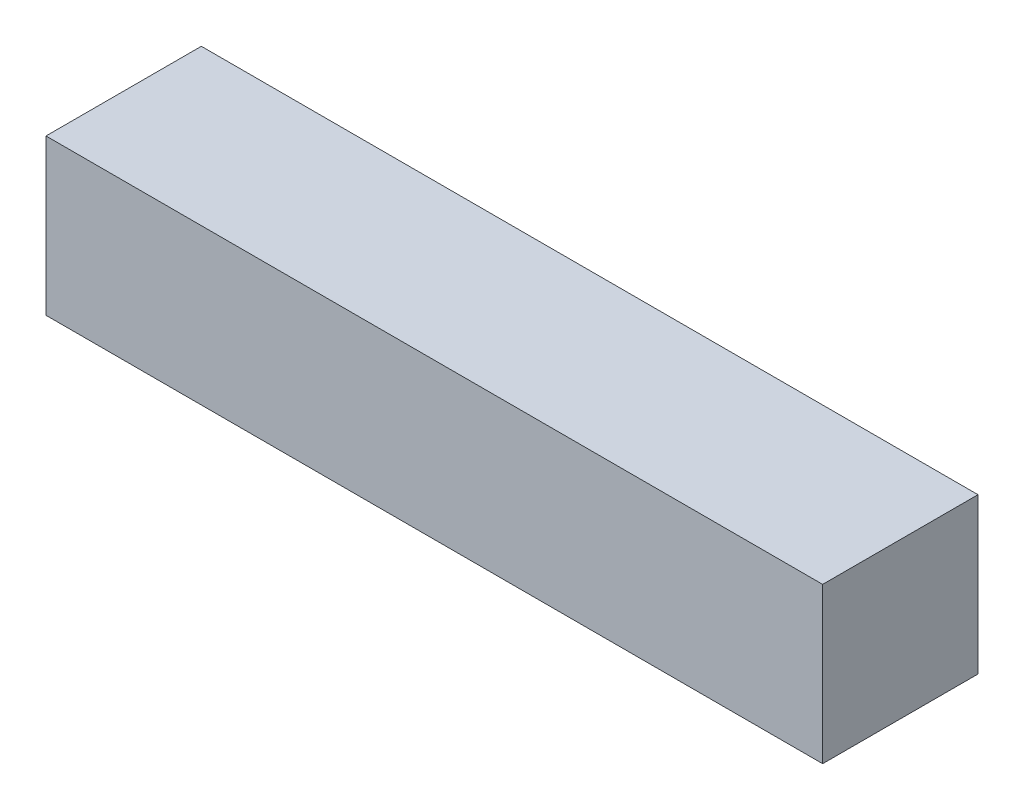
SolidWorks part; units mm, degrees
material "6061 Alloy"
ref_plane "Front Plane" through (0, 0, 0) normal (0, 0, 1) x (1, 0, 0)
ref_plane "Top Plane" through (0, 0, 0) normal (0, 1, 0) x (1, 0, 0)
ref_plane "Right Plane" through (0, 0, 0) normal (1, 0, 0) x (0, 0, -1)
sketch "Sketch1" plane through (0, 0, 0) normal (0, 0, 1) x (1, 0, 0)
  line L1 (-50, -10) -> (50, -10)
  line L2 (-50, -10) -> (-50, 10)
  line L3 (-50, 10) -> (50, 10)
  line L4 (50, -10) -> (50, 10)
  line L5 (-50, -10) -> (50, 10) construction
  line L6 (-50, 10) -> (50, -10) construction
  point P0 (0, 0)
  dimension "D1" = 20
  dimension "D2" = 100
extrude "Boss-Extrude1" add sketch "Sketch1" along normal blind 20
sketch3d "3DSketch1"
  point P0 (-52, 10, 20)
sketch "Sketch2" plane through (0, 10, 0) normal (0, 1, 0) x (1, 0, 0)
  line L1 (-44.6545, -45.8606) -> (43.0856, -45.8606)
  line L2 (-44.6545, -45.8606) -> (-44.6545, 32.7521)
  line L3 (-44.6545, 32.7521) -> (43.0856, 32.7521)
  line L4 (43.0856, -45.8606) -> (43.0856, 32.7521)
  line L5 (-44.6545, -45.8606) -> (43.0856, 32.7521) construction
  line L6 (-44.6545, 32.7521) -> (43.0856, -45.8606) construction
  point P0 (-0.7844, -6.5542)
